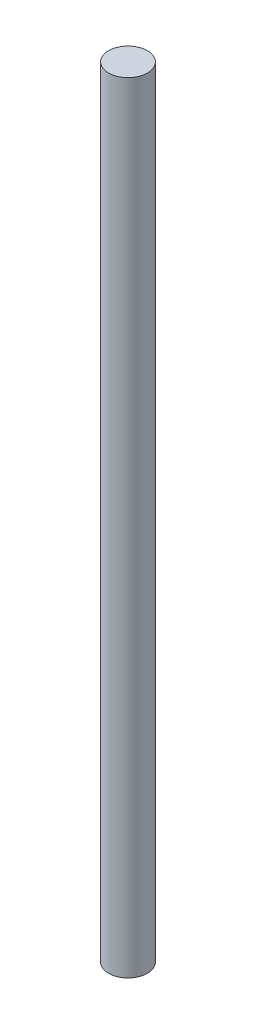
SolidWorks part; units mm, degrees
ref_plane "Front Plane" through (0, 0, 0) normal (0, 0, 1) x (1, 0, 0)
ref_plane "Top Plane" through (0, 0, 0) normal (0, 1, 0) x (1, 0, 0)
ref_plane "Right Plane" through (0, 0, 0) normal (1, 0, 0) x (0, 0, -1)
sketch "Sketch1" plane through (0, 0, 0) normal (0, 1, 0) x (1, 0, 0)
  circle A0 centre (0, 0) radius 4.975
  dimension "D1" = 9.95
extrude "Boss-Extrude1" add sketch "Sketch1" against normal blind 200
